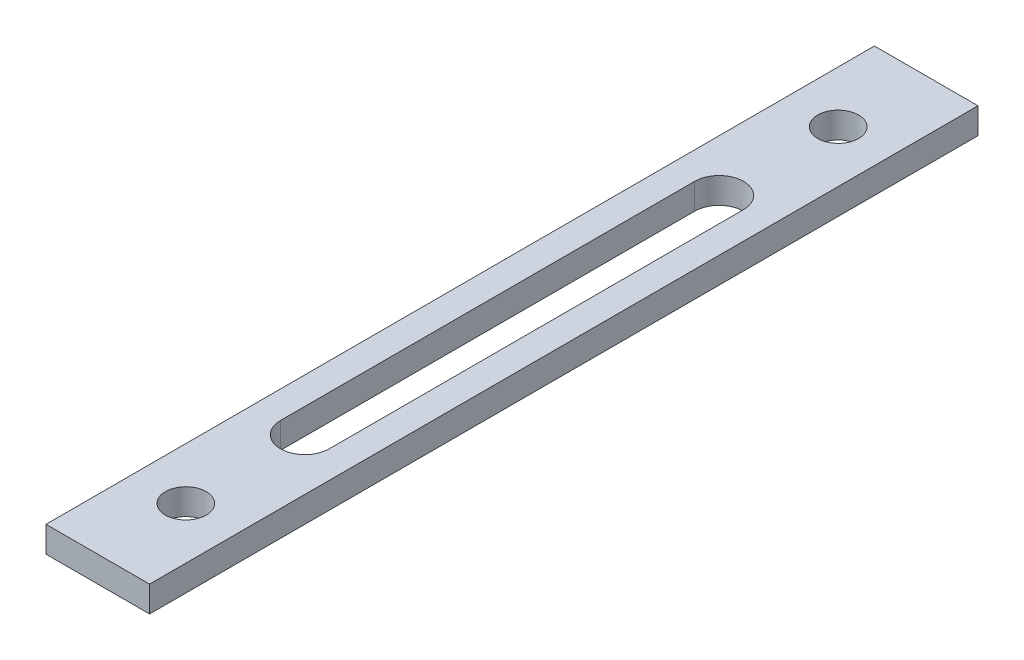
SolidWorks part; units mm, degrees
ref_plane "Front Plane" through (0, 0, 0) normal (0, 0, 1) x (1, 0, 0)
ref_plane "Top Plane" through (0, 0, 0) normal (0, 1, 0) x (1, 0, 0)
ref_plane "Right Plane" through (0, 0, 0) normal (1, 0, 0) x (0, 0, -1)
sketch "Sketch1" plane through (0, 0, 0) normal (0, 1, 0) x (1, 0, 0)
  line L1 (12.7, 101.6) -> (-12.7, 101.6)
  line L2 (12.7, 101.6) -> (12.7, -101.6)
  line L3 (12.7, -101.6) -> (-12.7, -101.6)
  line L4 (-12.7, 101.6) -> (-12.7, -101.6)
  line L5 (12.7, 101.6) -> (-12.7, -101.6) construction
  line L6 (12.7, -101.6) -> (-12.7, 101.6) construction
  point P0 (0, 0)
  dimension "D1" = 25.4
  dimension "D2" = 203.2
extrude "Boss-Extrude1" add sketch "Sketch1" along normal blind 6.35
sketch "Sketch2" plane through (0, 6.35, 0) normal (0, 1, 0) x (1, 0, 0)
  line L0 (0, -80) -> (0, 0) construction
  line L1 (0, 0) -> (0, 80) construction
  line L2 (-12.7, -101.6) -> (12.7, -101.6) construction
  circle A0 centre (0, -80) radius 5
  circle A1 centre (0, 80) radius 5
  dimension "D2" = 10
  dimension "D1" = 21.6
extrude "Cut-Extrude1" cut sketch "Sketch2" against normal through all
sketch "Sketch3" plane through (0, 6.35, 0) normal (0, 1, 0) x (1, 0, 0)
  line L0 (0, 50.8) -> (0, -50.8) construction
  line L1 (6, 50.8) -> (6, -50.8)
  line L2 (-6, 50.8) -> (-6, -50.8)
  line L3 (0, -80) -> (0, -50.8) construction
  arc A0 (6, 50.8) -> (-6, 50.8) centre (0, 50.8) ccw
  arc A1 (-6, -50.8) -> (6, -50.8) centre (0, -50.8) ccw
  point P2 (0, 0)
  dimension "D2" = 6
  dimension "D1" = 29.2
extrude "Cut-Extrude2" cut sketch "Sketch3" against normal through all
